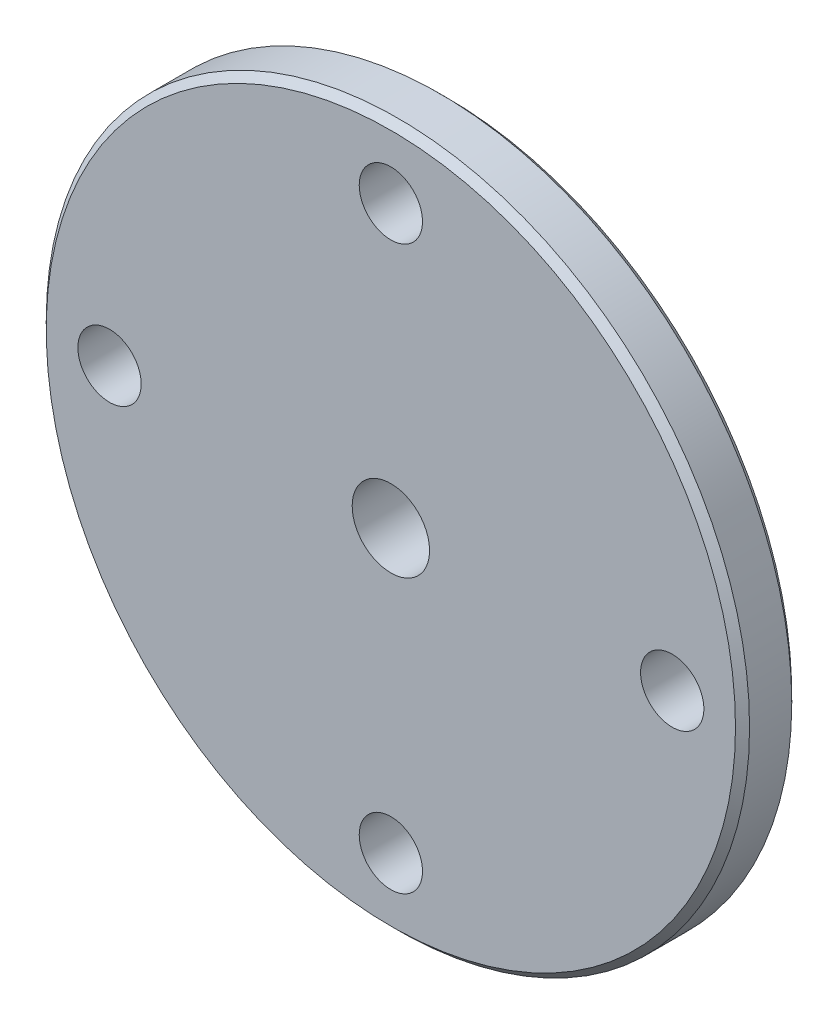
SolidWorks part; units mm, degrees
ref_plane "前视基准面" through (0, 0, 0) normal (0, 0, 1) x (1, 0, 0)
ref_plane "上视基准面" through (0, 0, 0) normal (0, 1, 0) x (1, 0, 0)
ref_plane "右视基准面" through (0, 0, 0) normal (1, 0, 0) x (0, 0, -1)
other "Configuration Table"
sketch "草图1" plane through (0, 0, 0) normal (0, 1, 0) x (1, 0, 0)
  line L0 (25, 0) -> (0, 0)
  line L1 (0, 0) -> (0, -4)
  line L2 (0, -4) -> (25, -4)
  line L3 (25, -4) -> (25, 0)
  line L4 (0, 0) -> (0, -4) construction
revolve "旋转1" add sketch "草图1" angle 360 about L4
hole_wizard "Ø5.5 (5.5) 直径孔1" positions "草图3" profile "草图2" hole size "Ø5.5" standard "ANSI Metric"
sketch "草图3" plane through (0, 0, 0) normal (0, 0, -1) x (-1, 0, 0)
  point P0 (0, 0)
sketch "草图2" plane through (0, 0, 0) normal (1, 0, 0) x (0, 1, 0)
  line L0 (0, 0) -> (0, 4)
  line L1 (0, 4) -> (2.75, 4)
  line L2 (2.75, 4) -> (2.75, 0)
  line L5 (2.75, 0) -> (0, 0)
  line L11 (0, -6.35) -> (0, 107.95) construction
  dimension "通孔孔直径" = 5.5
  dimension "通孔孔深度" = 4
hole_wizard "Ø4.5 (4.5) 直径孔1" positions "草图5" profile "草图4" hole size "Ø4.5" standard "ANSI Metric"
sketch "草图5" plane through (0, 0, 0) normal (0, 0, -1) x (-1, 0, 0)
  point P0 (0, 20)
  point P1 (-20, 0)
  point P2 (0, -20)
  point P3 (20, 0)
sketch "草图4" plane through (0, 20, 0) normal (1, 0, 0) x (0, 1, 0)
  line L0 (0, 0) -> (0, 4)
  line L1 (0, 4) -> (2.25, 4)
  line L2 (2.25, 4) -> (2.25, 0)
  line L5 (2.25, 0) -> (0, 0)
  line L11 (0, -6.35) -> (0, 107.95) construction
  dimension "通孔孔直径" = 4.5
  dimension "通孔孔深度" = 4
chamfer "倒角1" distance 0.5 angle 45 2 edges at (25, 0, 0) (25, 0, 4)
